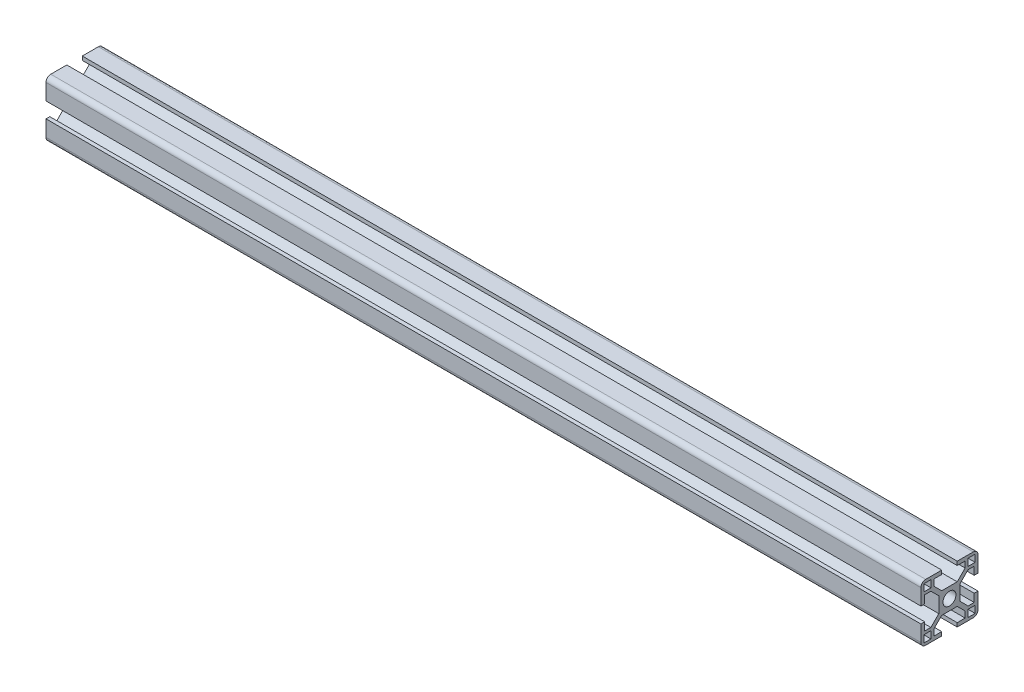
SolidWorks part; units mm, degrees
material "6061 Alloy"
ref_plane "Front Plane" through (0, 0, 0) normal (0, 0, 1) x (1, 0, 0)
ref_plane "Top Plane" through (0, 0, 0) normal (0, 1, 0) x (1, 0, 0)
ref_plane "Right Plane" through (0, 0, 0) normal (1, 0, 0) x (0, 0, -1)
sketch "Sketch1" plane through (0, 0, 0) normal (0, 1, 0) x (1, 0, 0)
  line L0 (0, 0) -> (460, 0)
  dimension "D1" = 460
other "T-slot profiles 3030_2(1)"
ref_plane "Plane1" through (0, 0, 0) normal (1, 0, 0) x (0, 0, -1)
sketch "Sketch17" plane through (0, 0, 0) normal (1, 0, 0) x (0, 0, -1)
  line L0 (0, 15) -> (0, -15) construction
  line L1 (-15, -15) -> (15, -15) construction
  line L2 (-15, -15) -> (-15, 15) construction
  line L3 (-15, 15) -> (15, 15) construction
  line L4 (15, -15) -> (15, 15) construction
  line L5 (-15, -15) -> (15, 15) construction
  line L6 (-15, 15) -> (15, -15) construction
  line L7 (-4.07, 5.6) -> (4.07, 5.6)
  line L8 (0, 0) -> (15, 0) construction
  line L9 (-4.07, -5.6) -> (4.07, -5.6)
  line L10 (5.6, -4.07) -> (5.6, 4.07)
  line L11 (-5.6, -4.07) -> (-5.6, 4.07)
  line L12 (-4.07, 5.6) -> (-8.25, 9.78)
  line L13 (4.07, 5.6) -> (8.25, 9.78)
  line L14 (-8.25, 9.78) -> (8.25, 9.78) construction
  line L15 (8.25, 9.78) -> (8.25, 13)
  line L16 (8.25, 13) -> (4.07, 13)
  line L17 (4.07, 13) -> (4.07, 15)
  line L18 (4.07, 15) -> (12.5, 15)
  line L19 (15, 12.5) -> (15, 4.07)
  line L20 (9.78, 8.25) -> (13, 8.25)
  line L21 (13, 8.25) -> (13, 4.07)
  line L22 (9.78, 8.25) -> (5.6, 4.07)
  line L23 (8.25, 9.78) -> (9.78, 8.25) construction
  line L24 (13, 4.07) -> (15, 4.07)
  line L25 (5.6, -4.07) -> (9.78, -8.25)
  line L26 (9.75, 13.5) -> (13.5, 13.5)
  line L27 (9.75, 13.5) -> (9.75, 9.75)
  line L28 (9.75, 9.75) -> (13.5, 9.75)
  line L29 (13.5, 13.5) -> (13.5, 9.75)
  line L30 (9.75, 13.5) -> (13.5, 9.75) construction
  line L31 (9.75, 9.75) -> (13.5, 13.5) construction
  line L32 (9.78, -8.25) -> (13, -8.25)
  line L33 (13, -8.25) -> (13, -4.07)
  line L34 (13, -4.07) -> (15, -4.07)
  line L35 (15, -4.07) -> (15, -12.5)
  line L36 (4.07, -5.6) -> (8.25, -9.78)
  line L37 (8.25, -9.78) -> (8.25, -13)
  line L38 (8.25, -13) -> (4.07, -13)
  line L39 (4.07, -13) -> (4.07, -15)
  line L40 (4.07, -15) -> (12.5, -15)
  line L41 (-4.07, -5.6) -> (-8.25, -9.78)
  line L42 (-8.25, -9.78) -> (-8.25, -13)
  line L43 (-8.25, -13) -> (-4.07, -13)
  line L44 (-4.07, -13) -> (-4.07, -15)
  line L45 (-4.07, -15) -> (-12.5, -15)
  line L46 (-8.25, 9.78) -> (-8.25, 13)
  line L47 (-8.25, 13) -> (-4.07, 13)
  line L48 (-4.07, 13) -> (-4.07, 15)
  line L49 (-4.07, 15) -> (-12.5, 15)
  line L50 (-5.6, 4.07) -> (-9.78, 8.25)
  line L51 (-9.78, 8.25) -> (-13, 8.25)
  line L52 (-13, 8.25) -> (-13, 4.07)
  line L53 (-13, 4.07) -> (-15, 4.07)
  line L54 (-15, 4.07) -> (-15, 12.5)
  line L55 (-5.6, -4.07) -> (-9.78, -8.25)
  line L56 (-9.78, -8.25) -> (-13, -8.25)
  line L57 (-13, -8.25) -> (-13, -4.07)
  line L58 (-13, -4.07) -> (-15, -4.07)
  line L59 (-15, -4.07) -> (-15, -12.5)
  line L60 (9.75, -9.75) -> (13.5, -9.75)
  line L61 (13.5, -13.5) -> (13.5, -9.75)
  line L62 (9.75, -13.5) -> (13.5, -13.5)
  line L63 (9.75, -13.5) -> (9.75, -9.75)
  line L64 (-9.75, 9.75) -> (-13.5, 9.75)
  line L65 (-13.5, 13.5) -> (-13.5, 9.75)
  line L66 (-9.75, 13.5) -> (-13.5, 13.5)
  line L67 (-9.75, 13.5) -> (-9.75, 9.75)
  line L68 (-9.75, -13.5) -> (-9.75, -9.75)
  line L69 (-9.75, -13.5) -> (-13.5, -13.5)
  line L70 (-13.5, -13.5) -> (-13.5, -9.75)
  line L71 (-9.75, -9.75) -> (-13.5, -9.75)
  arc A0 (-15, 12.5) -> (-12.5, 15) centre (-12.5, 12.5) cw
  arc A1 (12.5, -15) -> (15, -12.5) centre (12.5, -12.5) ccw
  arc A2 (15, 12.5) -> (12.5, 15) centre (12.5, 12.5) ccw
  arc A3 (-12.5, -15) -> (-15, -12.5) centre (-12.5, -12.5) cw
  circle A4 centre (0, 0) radius 3.4
  point P0 (0, 0)
  point P6 (0, 0)
  point P7 (-12.5, 12.5)
  point P26 (0, 5.6)
  point P32 (5.6, 0)
  point P44 (11.625, 11.625)
  dimension "D4" = 6.8
  dimension "D3" = 2.5
  dimension "D1" = 30
  dimension "D2" = 30
  dimension "D5" = 8.14
  dimension "D6" = 9.4
  dimension "D7" = 8.14
  dimension "D8" = 9.4
  dimension "D9" = 16.5
  dimension "D10" = 2
  dimension "D11" = 2
  dimension "D12" = 3.75
  dimension "D13" = 3.75
  dimension "D14" = 1.5
  dimension "D15" = 2
  dimension "D16" = 2
  dimension "D17" = 2
  dimension "D18" = 2
  dimension "D19" = 2
  dimension "D20" = 2
